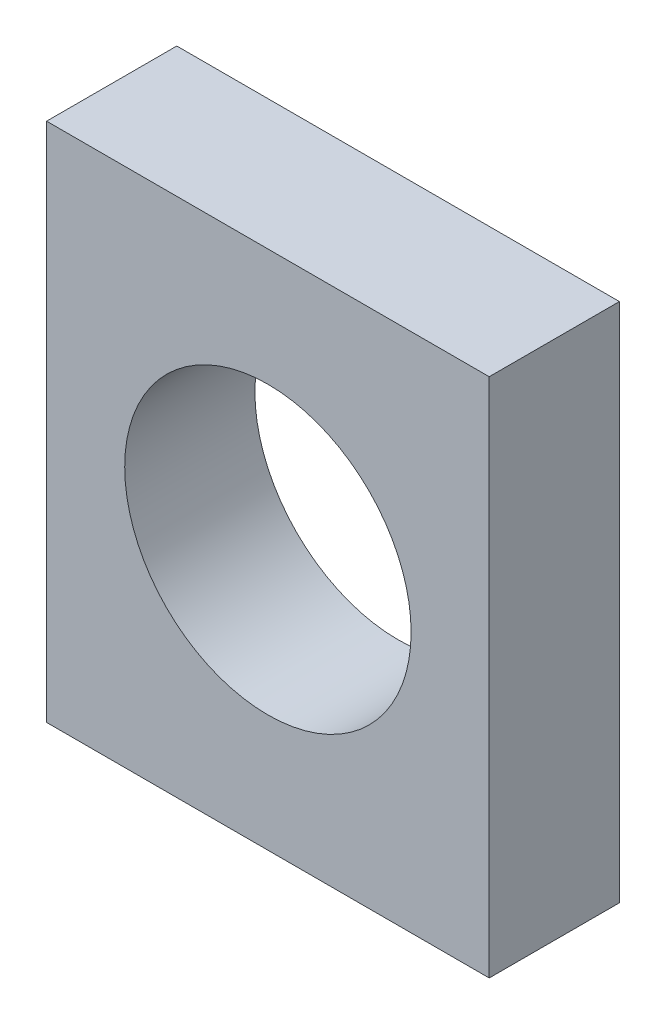
SolidWorks part; units mm, degrees
ref_plane "Plan de face" through (0, 0, 0) normal (0, 0, 1) x (1, 0, 0)
ref_plane "Plan de dessus" through (0, 0, 0) normal (0, 1, 0) x (1, 0, 0)
ref_plane "Plan de droite" through (0, 0, 0) normal (1, 0, 0) x (0, 0, -1)
sketch "Esquisse1" plane through (0, 0, 0) normal (0, 0, 1) x (1, 0, 0)
  line L0 (0, 0) -> (0, 62.3308) construction
  line L1 (-8.5, 10) -> (8.5, 10)
  line L2 (-8.5, 10) -> (-8.5, -10)
  line L3 (-8.5, -10) -> (8.5, -10)
  line L4 (8.5, 10) -> (8.5, -10)
  line L5 (0, 0) -> (30.6628, 0) construction
  circle A0 centre (0, 0) radius 5.5
  dimension "D1" = 11
  dimension "D2" = 17
  dimension "D3" = 20
extrude "Extrusion1" add sketch "Esquisse1" along normal blind 5
